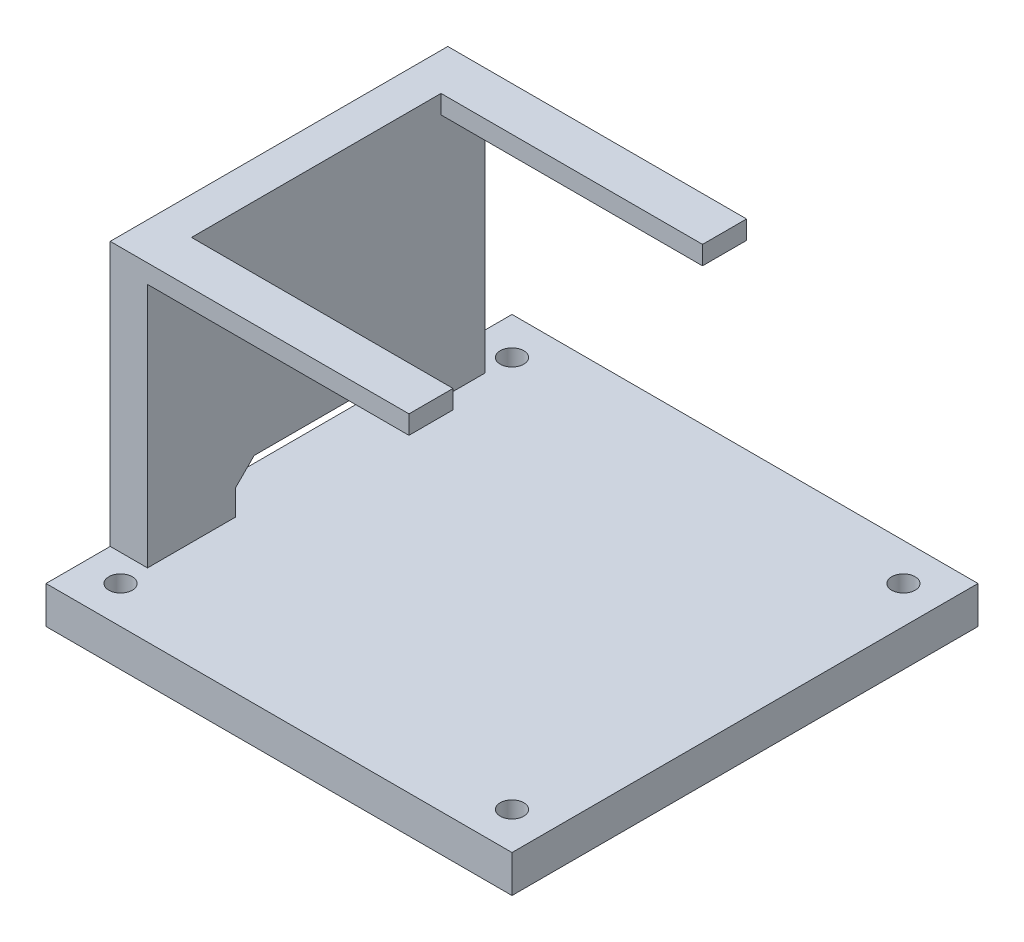
SolidWorks part; units mm, degrees
ref_plane "Front Plane" through (0, 0, 0) normal (0, 0, 1) x (1, 0, 0)
ref_plane "Top Plane" through (0, 0, 0) normal (0, 1, 0) x (1, 0, 0)
ref_plane "Right Plane" through (0, 0, 0) normal (1, 0, 0) x (0, 0, -1)
sketch "Sketch1" plane through (0, 0, 0) normal (0, 1, 0) x (1, 0, 0)
  line L1 (-15.875, -15.875) -> (15.875, -15.875)
  line L2 (-15.875, -15.875) -> (-15.875, 15.875)
  line L3 (-15.875, 15.875) -> (15.875, 15.875)
  line L4 (15.875, -15.875) -> (15.875, 15.875)
  line L5 (-15.875, -15.875) -> (15.875, 15.875) construction
  line L6 (-15.875, 15.875) -> (15.875, -15.875) construction
  point P0 (0, 0)
  dimension "D1" = 31.75
  dimension "D2" = 31.75
extrude "Boss-Extrude1" add sketch "Sketch1" along normal blind 2.54
sketch "Sketch3" plane through (0, 2.54, 0) normal (0, 1, 0) x (1, 0, 0)
  line L9 (-13.335, -8.5) -> (-15.875, -8.5)
  line L10 (-13.335, -11.5) -> (-15.875, -11.5)
  line L11 (-15.875, -8.5) -> (-15.875, -11.5)
  line L12 (-13.335, 8.5) -> (-15.875, 8.5)
  line L13 (-13.335, 11.5) -> (-15.875, 11.5)
  line L14 (-15.875, 8.5) -> (-15.875, 11.5)
  line L15 (-13.335, -11.5) -> (-13.335, -8.5)
  line L16 (-13.335, 8.5) -> (-13.335, 11.5)
  line L17 (-15.875, 15.875) -> (-15.875, -15.875) construction
  point P10 (-15.875, 0)
  dimension "D1" = 2.54
  dimension "D2" = 3
  dimension "D3" = 8.5
  dimension "D4" = 8.5
extrude "Boss-Extrude2" add sketch "Sketch3" along normal blind 18
sketch "Sketch6" plane through (0, 0, 11.5) normal (0, 0, 1) x (1, 0, 0)
  line L0 (-13.335, 20.54) -> (-13.335, 19.27)
  line L1 (-13.335, 19.27) -> (4.4798, 19.27)
  line L2 (-13.335, 20.54) -> (4.4823, 20.54)
  line L3 (4.4823, 20.54) -> (4.4798, 19.27)
  line L5 (-13.335, 20.54) -> (-13.335, 2.54) construction
  dimension "D1" = 90
  dimension "D2" = 1.27
extrude "Boss-Extrude3" add sketch "Sketch6" against normal blind 3
pattern_linear "LPattern1" count 2 spacing 20 along (0, 0, -1) of "Boss-Extrude3"
sketch "Sketch7" plane through (0, 2.54, 0) normal (0, 1, 0) x (1, 0, 0)
  line L0 (15.875, -15.875) -> (15.875, 15.875) construction
  line L1 (15.875, 15.875) -> (-15.875, 15.875) construction
  line L2 (-15.875, -15.875) -> (15.875, -15.875) construction
  line L3 (-15.875, -11.5) -> (-15.875, -15.875) construction
  circle A0 centre (13.335, 13.335) radius 0.8
  circle A1 centre (-13.335, 13.335) radius 0.8
  circle A2 centre (-13.335, -13.335) radius 0.8
  circle A3 centre (13.335, -13.335) radius 0.8
  point P7 (0, 0)
  point P8 (0, 0)
  point P18 (0, 0)
  dimension "D1" = 2.54
  dimension "D2" = 2.54
  dimension "D5" = 2.54
  dimension "D6" = 2.54
  dimension "D7" = 2.54
  dimension "D3" = 2
  dimension "D4" = 2
extrude "Cut-Extrude1" cut sketch "Sketch7" against normal through all
sketch "Sketch8" plane through (0, 0, 8.5) normal (0, 0, -1) x (-1, 0, 0)
  line L1 (13.335, 20.54) -> (15.875, 20.54)
  line L2 (13.335, 20.54) -> (13.335, 2.54)
  line L3 (13.335, 2.54) -> (15.875, 2.54)
  line L4 (15.875, 20.54) -> (15.875, 2.54)
extrude "Boss-Extrude4" add sketch "Sketch8" along normal up to surface (17 mm away) up to face at (-8.243, 14.1167, -8.5)
sketch "Sketch10" plane through (-13.335, 0, 0) normal (1, 0, 0) x (0, 0, -1)
  line L0 (-11.5, 2.54) -> (11.5, 2.54) construction
  line L1 (5.5, 2.54) -> (-5.5, 2.54)
  line L2 (5.5, 2.54) -> (5.5, 5.54)
  line L3 (5.5, 5.54) -> (-5.5, 5.54)
  line L4 (-5.5, 2.54) -> (-5.5, 5.54)
  point P6 (0, 2.54)
  point P7 (0, 2.54)
  dimension "D1" = 3
  dimension "D2" = 11
extrude "Cut-Extrude2" cut sketch "Sketch10" against normal blind 2.54 contours L3 L4 L1 L2
chamfer "Chamfer1" distance 1.27 angle 45 2 edges at (-14.605, 5.54, 5.5) (-14.605, 5.54, -5.5)
